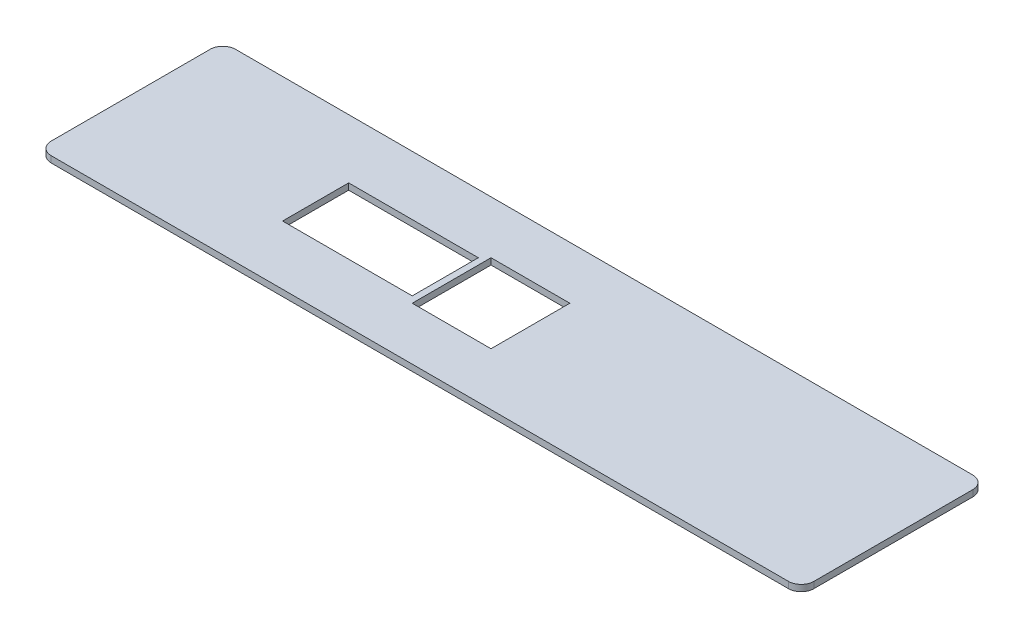
SolidWorks part; units mm, degrees
ref_plane "Front Plane" through (0, 0, 0) normal (0, 0, 1) x (1, 0, 0)
ref_plane "Top Plane" through (0, 0, 0) normal (0, 1, 0) x (1, 0, 0)
ref_plane "Right Plane" through (0, 0, 0) normal (1, 0, 0) x (0, 0, -1)
sketch "Sketch1" plane through (0, 0, 0) normal (0, 1, 0) x (1, 0, 0)
  line L1 (0, 14.5) -> (120, 14.5)
  line L2 (0, 14.5) -> (0, -14.5)
  line L3 (0, -14.5) -> (120, -14.5)
  line L4 (120, 14.5) -> (120, -14.5)
  line L5 (29.5, 5) -> (49.5, 5)
  line L6 (29.5, 5) -> (29.5, -5)
  line L7 (29.5, -5) -> (49.5, -5)
  line L8 (49.5, 5) -> (49.5, -5)
  line L9 (50.5, 6) -> (62.5, 6)
  line L10 (50.5, 6) -> (50.5, -6)
  line L11 (50.5, -6) -> (62.5, -6)
  line L12 (62.5, 6) -> (62.5, -6)
  point P4 (0, 0)
  point P10 (29.5, 0)
  point P15 (50.5, 0)
  dimension "D1" = 29
  dimension "D2" = 120
  dimension "D3" = 29.5
  dimension "D4" = 20
  dimension "D5" = 10
  dimension "D6" = 12
  dimension "D7" = 12
  dimension "D8" = 1
sketch "Sketch2" plane through (0, 0, 0) normal (0, 1, 0) x (1, 0, 0)
  line L0 (0, 12.5) -> (0, -12.5)
  line L1 (2, -14.5) -> (118, -14.5)
  line L2 (120, -12.5) -> (120, 12.5)
  line L3 (118, 14.5) -> (2, 14.5)
  line L4 (49.5, 5) -> (49.5, -5) construction
  line L5 (29.1, 5.2) -> (49.5, 5.2)
  line L6 (29.1, 5.2) -> (29.1, -5.2)
  line L7 (29.1, -5.2) -> (49.5, -5.2)
  line L8 (49.5, 5.2) -> (49.5, -5.2)
  line L9 (29.5, 5) -> (29.5, -5) construction
  line L10 (29.5, 5) -> (49.5, 5) construction
  line L11 (29.5, -5) -> (49.5, -5) construction
  line L12 (50.5, 6) -> (50.5, -6) construction
  line L13 (50.5, 6.2) -> (62.9, 6.2)
  line L14 (50.5, 6.2) -> (50.5, -6.2)
  line L15 (50.5, -6.2) -> (62.9, -6.2)
  line L16 (62.9, 6.2) -> (62.9, -6.2)
  line L17 (50.5, 6) -> (62.5, 6) construction
  line L18 (50.5, -6) -> (62.5, -6) construction
  line L19 (62.5, 6) -> (62.5, -6) construction
  arc A0 (118, 14.5) -> (120, 12.5) centre (118, 12.5) cw
  arc A1 (120, -12.5) -> (118, -14.5) centre (118, -12.5) cw
  arc A2 (2, -14.5) -> (0, -12.5) centre (2, -12.5) cw
  arc A3 (2, 14.5) -> (0, 12.5) centre (2, 12.5) ccw
  point P10 (120, 14.5)
  point P13 (120, -14.5)
  point P16 (0, -14.5)
  point P19 (0, 14.5)
  dimension "D1" = 2
  dimension "D2" = 0.4
  dimension "D3" = 0.2
  dimension "D4" = 0.2
  dimension "D5" = 0.2
  dimension "D6" = 0.2
  dimension "D7" = 0.4
extrude "Boss-Extrude1" add sketch "Sketch2" along normal blind 1
